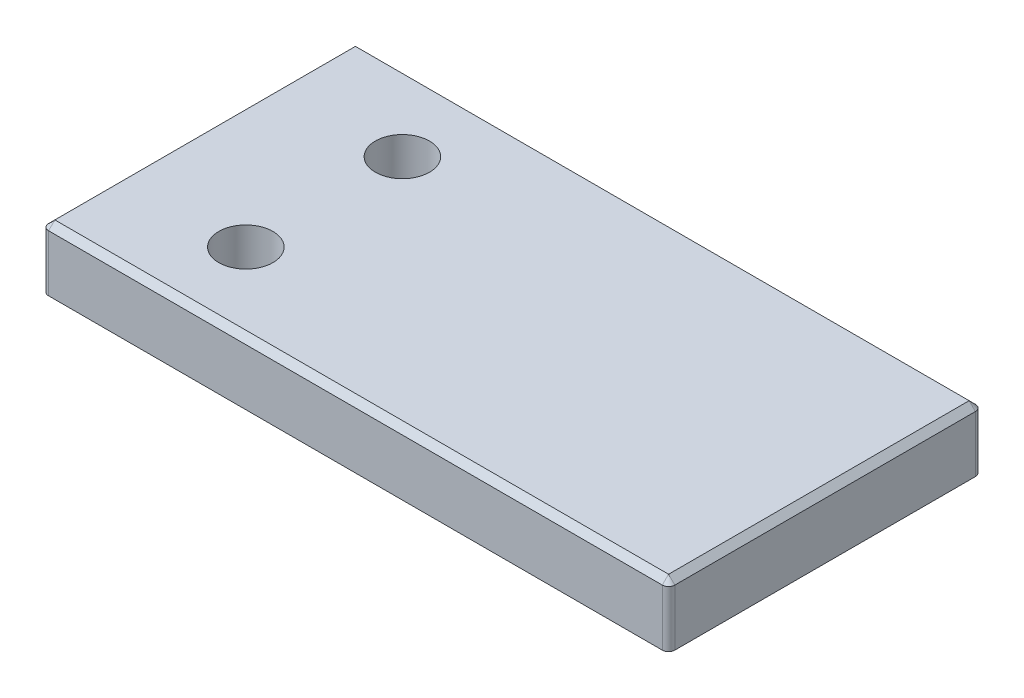
SolidWorks part; units mm, degrees
ref_plane "前基準面" through (0, 0, 0) normal (0, 0, 1) x (1, 0, 0)
ref_plane "上基準面" through (0, 0, 0) normal (0, 1, 0) x (1, 0, 0)
ref_plane "右基準面" through (0, 0, 0) normal (1, 0, 0) x (0, 0, -1)
ref_plane "平面1"
sketch "草圖1" plane through (0, 0, 0) normal (0, 1, 0) x (-1, 0, 0)
  line L0 (50, -25) -> (-50, -25)
  line L1 (-50, -25) -> (-50, 25)
  line L2 (-50, 25) -> (50, 25)
  line L3 (50, 25) -> (50, -25)
  dimension "D1" = 100
  dimension "D2" = 50
extrude "擠出1" add sketch "草圖1" along normal blind 10
fillet "圓角1" radius 1 4 edges at (-50, 5, 25) (-50, 5, -25) (50, 5, -25) (50, 5, 25)
chamfer "倒角2" distance 1 distance2 1 8 edges at (0, 10, 25) (49.7071, 10, 24.7071) (50, 10, 0) (49.7071, 10, -24.7071) (0, 10, -25) (-49.7071, 10, -24.7071) (-50, 10, 0) (-49.7071, 10, 24.7071)
hole_wizard "孔1" positions "草圖3" profile "草圖2" legacy
sketch "草圖3" plane through (0, 10, 0) normal (0, 1, 0) x (1, 0, 0)
  point P1 (-30, 12.5)
  point P2 (-30, -12.5)
sketch "草圖2" plane through (-30, 10, -12.5) normal (1, 0, 0) x (0, 0, 1)
  line L0 (0, 0) -> (0, 28.7978)
  line L1 (0, 28.7978) -> (4.3235, 26.2)
  line L2 (4.3235, 26.2) -> (4.3235, 0)
  line L4 (4.3235, 0) -> (0, 0)
  line L6 (0, 28.7978) -> (-4.3235, 26.2) construction
  line L7 (0, -4.2442) -> (0, 117.3081) construction
  dimension "直徑" = 8.647
  dimension "深度" = 26.2
  dimension "導頭角度" = 118
cosmetic thread "裝飾螺紋線1" parameters "D1"=10, "D2"=10.34
cosmetic thread "裝飾螺紋線2" parameters "D1"=10, "D2"=10.34
